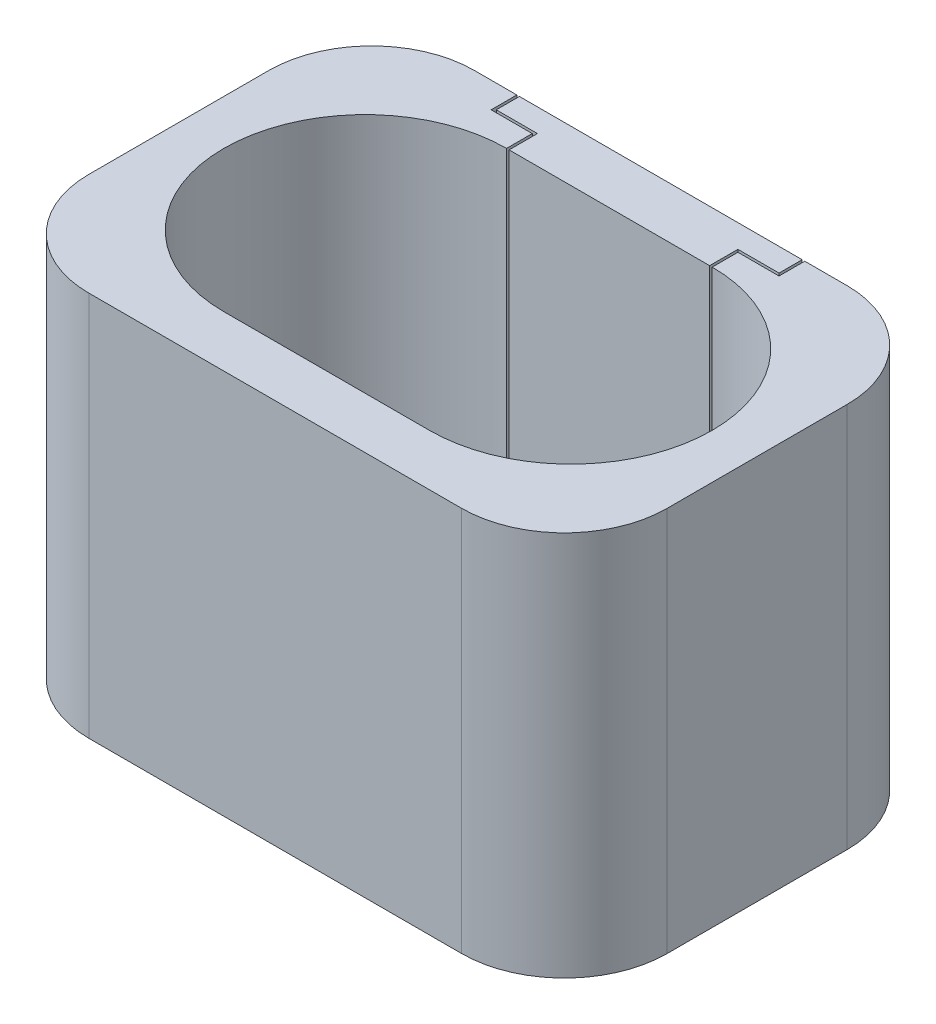
SolidWorks part; units mm, degrees
ref_plane "Front Plane" through (0, 0, 0) normal (0, 0, 1) x (1, 0, 0)
ref_plane "Top Plane" through (0, 0, 0) normal (0, 1, 0) x (1, 0, 0)
ref_plane "Right Plane" through (0, 0, 0) normal (1, 0, 0) x (0, 0, -1)
sketch "Sketch1" plane through (0, 0, 0) normal (0, 1, 0) x (1, 0, 0)
  line L0 (-22.5, 15) -> (-22.5, 0)
  line L1 (-22.5, 0) -> (0, 0)
  line L3 (-22.5, 15) -> (0, 15)
  line L5 (0, 15) -> (0, 0)
  dimension "D1" = 22.5
  dimension "D2" = 15
extrude "Boss-Extrude1" add sketch "Sketch1" along normal mid plane 15
sketch "Sketch2" plane through (0, 7.5, 0) normal (0, 1, 0) x (1, 0, 0)
  line L0 (-15.25, 7.5) -> (-7.25, 7.5) construction
  line L1 (-15.25, 13) -> (-7.25, 13)
  line L2 (-15.25, 2) -> (-7.25, 2)
  line L3 (-22.5, 15) -> (-22.5, 0) construction
  line L4 (0, 15) -> (-22.5, 15) construction
  arc A0 (-15.25, 13) -> (-15.25, 2) centre (-15.25, 7.5) ccw
  arc A1 (-7.25, 2) -> (-7.25, 13) centre (-7.25, 7.5) ccw
  point P2 (-11.25, 7.5)
  point P9 (-22.5, 7.5)
  point P14 (-11.25, 15)
  dimension "D1" = 11
  dimension "D2" = 8
extrude "Cut-Extrude1" cut sketch "Sketch2" against normal through all
sketch "Sketch3" plane through (0, 0, -15) normal (0, 0, -1) x (-1, 0, 0)
  line L0 (0, 7.5) -> (22.5, 7.5) construction
  line L1 (7.25, 7.5) -> (15.25, 7.5)
  line L2 (7.25, 7.5) -> (7.25, -7.5)
  line L3 (7.25, -7.5) -> (15.25, -7.5)
  line L4 (15.25, 7.5) -> (15.25, -7.5)
  line L5 (0, -7.5) -> (22.5, -7.5) construction
  point P6 (11.25, -7.5)
  point P9 (11.25, -7.5)
  dimension "D1" = 8
extrude "Cut-Extrude2" cut sketch "Sketch3" against normal up to next
sketch "Sketch4" plane through (0, 7.5, 0) normal (0, 1, 0) x (1, 0, 0)
  line L0 (-15.25, 13) -> (-15.25, 15) construction
  line L1 (-15.25, 15) -> (-16.85, 15)
  line L2 (-15.25, 15) -> (-15.25, 14)
  line L3 (-15.25, 14) -> (-16.85, 14)
  line L4 (-16.85, 15) -> (-16.85, 14)
  point P7 (0, 0)
  point P8 (-15.25, 14)
  dimension "D2" = 1.6
extrude "Cut-Extrude3" cut sketch "Sketch4" against normal blind 15
ref_plane "Plane1" through (-11.25, 0, 0) normal (-1, 0, 0) x (0, 0, 1)
mirror "Mirror1" about plane through (-11.25, 0, 0) normal (-1, 0, 0) of "Cut-Extrude3"
sketch "Sketch5" plane through (0, 7.5, 0) normal (0, 1, 0) x (1, 0, 0)
  line L0 (-11.25, 15) -> (-15.15, 15)
  line L1 (-11.25, 3.85) -> (-11.25, -3.85) construction
  line L3 (-15.15, 15) -> (-16.75, 15)
  line L4 (-16.75, 15) -> (-16.75, 14.1)
  line L5 (-16.75, 14.1) -> (-15.15, 14.1)
  line L6 (-15.15, 14.1) -> (-15.15, 13)
  line L7 (-15.15, 13) -> (-11.25, 13)
  line L8 (-11.25, 13) -> (-11.25, 15)
  line L10 (-16.85, 14) -> (-15.25, 14) construction
  line L11 (-16.85, 15) -> (-16.85, 14) construction
  line L13 (-15.25, 13) -> (-15.25, 14) construction
  line L14 (-16.85, 15) -> (-22.5, 15) construction
  line L15 (-16.85, 15) -> (-22.5, 15) construction
  dimension "D2" = 0.1
  dimension "D3" = 0.1
  dimension "D5" = 0.1
extrude "Boss-Extrude2" add sketch "Sketch5" against normal through all separate body
mirror "Mirror3" about plane through (-11.25, 0, 0) normal (-1, 0, 0) of bodies 106
fillet "Fillet1" radius 4 4 edges at (0, 0, -15) (0, 0, 0) (-22.5, 0, 0) (-22.5, 0, -15)
